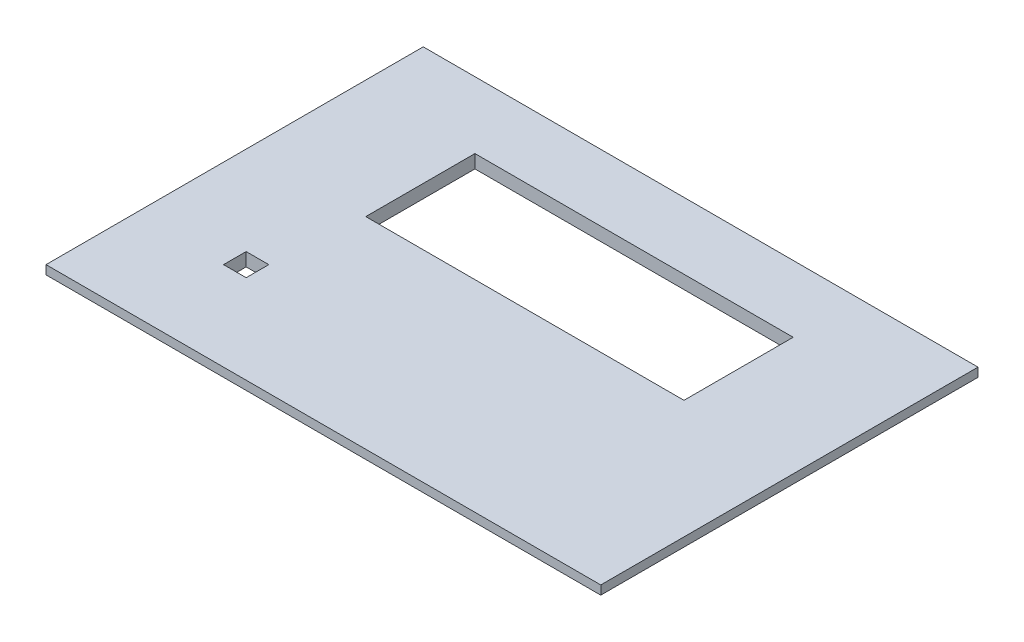
SolidWorks part; units mm, degrees
ref_plane "Plano frontal" through (0, 0, 0) normal (0, 0, 1) x (1, 0, 0)
ref_plane "Plano superior" through (0, 0, 0) normal (0, 1, 0) x (1, 0, 0)
ref_plane "Plano direito" through (0, 0, 0) normal (1, 0, 0) x (0, 0, -1)
sketch "Esboço1" plane through (0, 0, 0) normal (0, 1, 0) x (1, 0, 0)
  line L1 (-57.95, -37.95) -> (57.95, -37.95)
  line L2 (-57.95, -37.95) -> (-57.95, 37.95)
  line L3 (-57.95, 37.95) -> (57.95, 37.95)
  line L4 (57.95, -37.95) -> (57.95, 37.95)
  line L5 (-57.95, -37.95) -> (57.95, 37.95) construction
  line L6 (-57.95, 37.95) -> (57.95, -37.95) construction
  point P0 (0, 0)
  dimension "D1" = 115.9
  dimension "D2" = 75.9
extrude "Ressalto-extrusão1" add sketch "Esboço1" along normal blind 1
sketch "Esboço2" plane through (0, 1, 0) normal (0, 1, 0) x (1, 0, 0)
  line L1 (-62.5, -42.5) -> (62.5, -42.5)
  line L2 (-62.5, -42.5) -> (-62.5, 42.5)
  line L3 (-62.5, 42.5) -> (62.5, 42.5)
  line L4 (62.5, -42.5) -> (62.5, 42.5)
  line L5 (-62.5, -42.5) -> (62.5, 42.5) construction
  line L6 (-62.5, 42.5) -> (62.5, -42.5) construction
  point P0 (0, 0)
  dimension "D1" = 125
  dimension "D2" = 85
extrude "Ressalto-extrusão2" add sketch "Esboço2" along normal blind 2
sketch "Esboço3" plane through (0, 3, 0) normal (0, 1, 0) x (1, 0, 0)
  line L0 (0, 0) -> (0, 42.5) construction
  line L1 (-35.85, 27.5) -> (35.85, 27.5)
  line L2 (-35.85, 27.5) -> (-35.85, 2.9)
  line L3 (-35.85, 2.9) -> (35.85, 2.9)
  line L4 (35.85, 27.5) -> (35.85, 2.9)
  line L5 (-35.85, 27.5) -> (35.85, 2.9) construction
  line L6 (-35.85, 2.9) -> (35.85, 27.5) construction
  line L7 (62.5, 42.5) -> (-62.5, 42.5) construction
  line L8 (-62.5, 42.5) -> (-62.5, -42.5) construction
  line L10 (-42.5, -22.5) -> (-37.4, -22.5)
  line L11 (-42.5, -22.5) -> (-42.5, -17.4)
  line L12 (-42.5, -17.4) -> (-37.4, -17.4)
  line L13 (-37.4, -22.5) -> (-37.4, -17.4)
  line L14 (-42.5, -22.5) -> (-37.4, -17.4) construction
  line L15 (-42.5, -17.4) -> (-37.4, -22.5) construction
  line L16 (-62.5, -42.5) -> (62.5, -42.5) construction
  point P0 (0, 15.2)
  point P11 (-39.95, -19.95)
  dimension "D1" = 71.7
  dimension "D2" = 24.6
  dimension "D3" = 15
  dimension "D4" = 5.1
  dimension "D5" = 5.1
  dimension "D6" = 20
  dimension "D7" = 20
extrude "Corte-extrusão1" cut sketch "Esboço3" against normal through all
